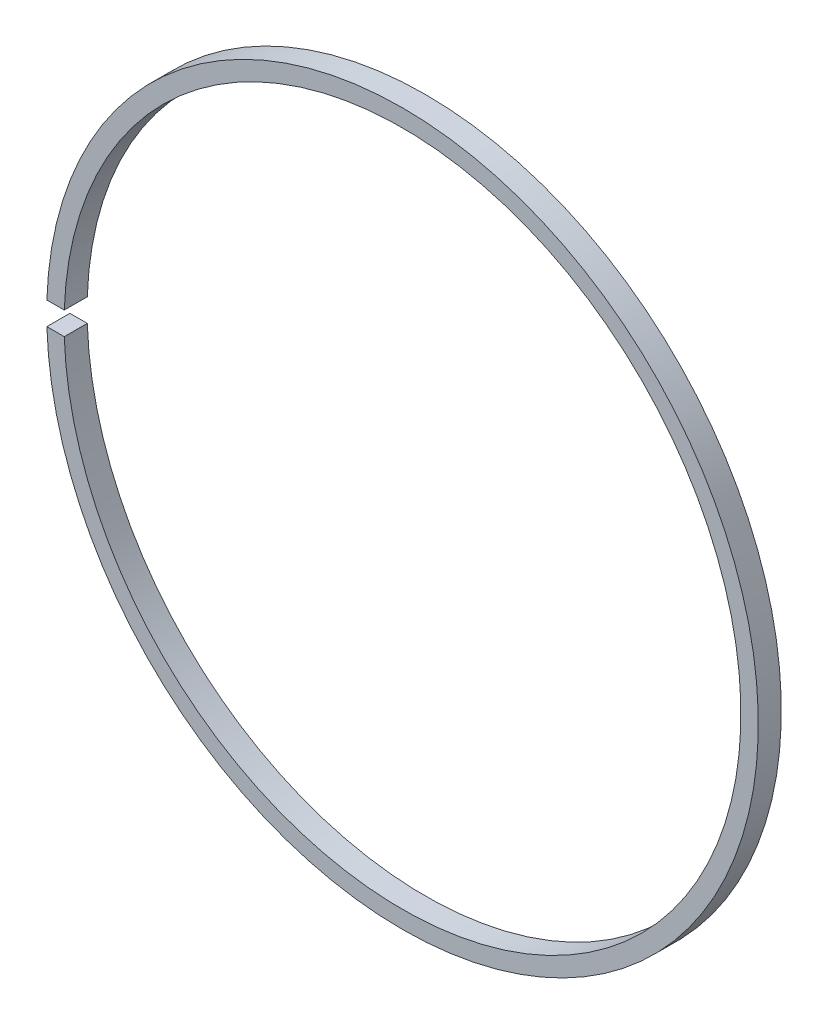
SolidWorks part; units mm, degrees
ref_plane "Front Plane" through (0, 0, 0) normal (0, 0, 1) x (1, 0, 0)
ref_plane "Top Plane" through (0, 0, 0) normal (0, 1, 0) x (1, 0, 0)
ref_plane "Right Plane" through (0, 0, 0) normal (1, 0, 0) x (0, 0, -1)
sketch "Sketch1" plane through (0, 0, 0) normal (0, 0, 1) x (1, 0, 0)
  circle A0 centre (0, 0) radius 46.6852
  circle A1 centre (0, 0) radius 49.0855
  dimension "D1" = 93.3704
  dimension "D2" = 98.171
extrude "Boss-Extrude1" add sketch "Sketch1" along normal blind 3.175
sketch "Sketch2" plane through (0, 0, 0) normal (0, 0, -1) x (-1, 0, 0)
  line L1 (0, -1.5875) -> (50.8, -1.5875)
  line L2 (0, -1.5875) -> (0, 1.5875)
  line L3 (0, 1.5875) -> (50.8, 1.5875)
  line L4 (50.8, -1.5875) -> (50.8, 1.5875)
  point P4 (0, 0)
  dimension "D1" = 3.175
  dimension "D2" = 50.8
extrude "Cut-Extrude1" cut sketch "Sketch2" against normal through all
